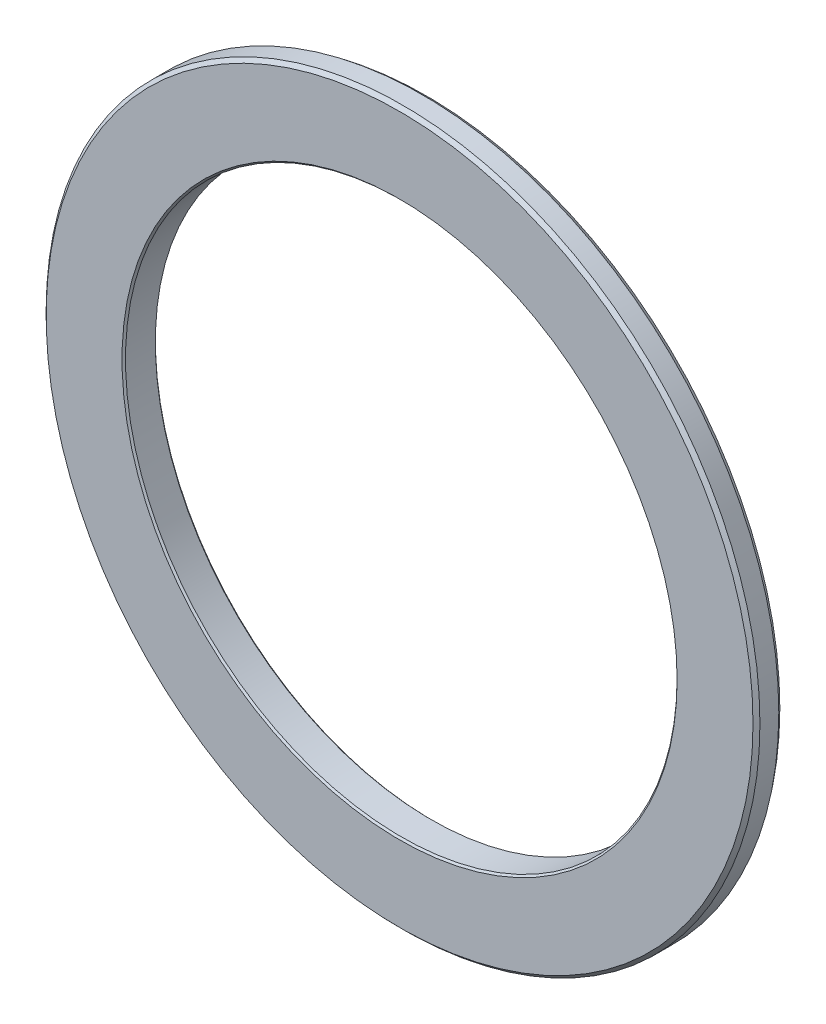
SolidWorks part; units mm, degrees
material "1060 Сплав"
ref_plane "Спереди" through (0, 0, 0) normal (0, 0, 1) x (1, 0, 0)
ref_plane "Сверху" through (0, 0, 0) normal (0, 1, 0) x (1, 0, 0)
ref_plane "Справа" through (0, 0, 0) normal (1, 0, 0) x (0, 0, -1)
sketch "Эскиз1" plane through (0, 0, 0) normal (0, 0, 1) x (1, 0, 0)
  circle A0 centre (0, 0) radius 20.575
  circle A1 centre (0, 0) radius 15.9
  dimension "D1" = 41.15
  dimension "D2" = 31.8
extrude "Бобышка-Вытянуть1" add sketch "Эскиз1" along normal blind 1.92
chamfer "Фаска1" distance 3 distance2 0.4 1 edges at (20.575, 0, 0)
chamfer "Фаска2" distance 0.2 angle 45 2 edges at (20.575, 0, 1.92) (20.575, 0, 0.4)
chamfer "Фаска3" distance 0.1 angle 45 2 edges at (15.9, 0, 0) (15.9, 0, 1.92)
